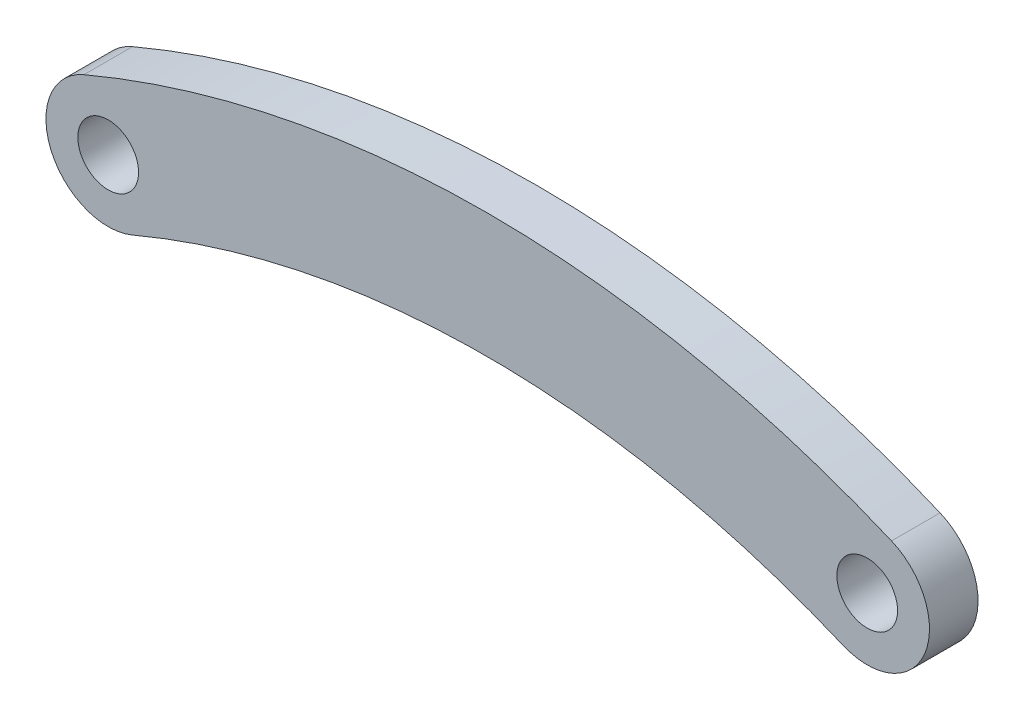
SolidWorks part; units mm, degrees
ref_plane "Front Plane" through (0, 0, 0) normal (0, 0, 1) x (1, 0, 0)
ref_plane "Top Plane" through (0, 0, 0) normal (0, 1, 0) x (1, 0, 0)
ref_plane "Right Plane" through (0, 0, 0) normal (1, 0, 0) x (0, 0, -1)
sketch "Sketch3" plane through (0, 0, 0) normal (0, 0, 1) x (1, 0, 0)
  arc A0 (0, 0) -> (25, 0) centre (12.5, -29.5119) cw construction
  arc A1 (25.7995, 1.8877) -> (-0.7995, 1.8877) centre (12.5, -29.5119) ccw
  arc A2 (24.2005, -1.8877) -> (0.7995, -1.8877) centre (12.5, -29.5119) ccw
  arc A3 (24.2005, -1.8877) -> (25.7995, 1.8877) centre (25, 0) ccw
  arc A4 (-0.7995, 1.8877) -> (0.7995, -1.8877) centre (0, 0) ccw
  circle A5 centre (0, 0) radius 1
  circle A6 centre (25, 0) radius 1
  point P3 (12.5, 2.5381)
  point P12 (12.5, 0.4881)
  dimension "D2" = 2.05
  dimension "D3" = 30
  dimension "D1" = 2
extrude "Boss-Extrude1" add sketch "Sketch3" along normal blind 1.6
